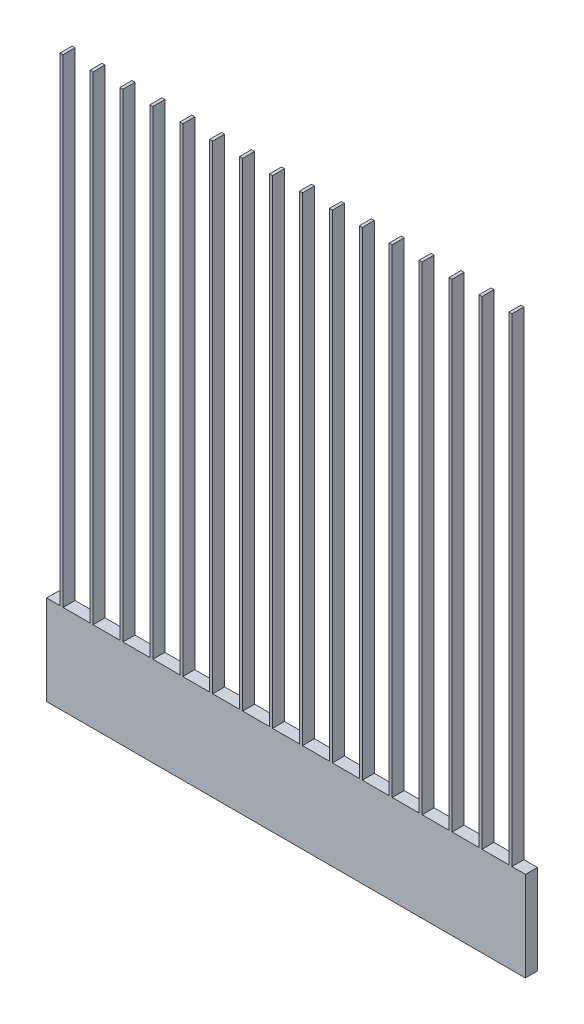
SolidWorks part; units mm, degrees
ref_plane "Front Plane" through (0, 0, 0) normal (1, 0, 0) x (0, 1, 0)
ref_plane "Top Plane" through (0, 0, 0) normal (0, 0, 1) x (0, 1, 0)
ref_plane "Right Plane" through (0, 0, 0) normal (0, 1, 0) x (-1, 0, 0)
sketch "Sketch1" plane through (0, 0, 0) normal (0, 0, 1) x (0, 1, 0)
  line L1 (0, 0) -> (10, 0) construction
  line L2 (0, 0) -> (0, -10) construction
  line L3 (0, -10) -> (10, -10) construction
  line L4 (10, 0) -> (10, -10) construction
  line L5 (0.5, -1) -> (2, -1)
  line L6 (0.5, -1) -> (0.5, -9)
  line L7 (0.5, -9) -> (2, -9)
  line L8 (2, -1) -> (2, -9)
  point P11 (1.8074, -10.4413)
  dimension "D1" = 10
  dimension "D2" = 10
  dimension "D3" = 1
  dimension "D4" = 1
  dimension "D5" = 0.5
  dimension "D6" = 1.5
extrude "Boss-Extrude1" add sketch "Sketch1" along normal blind 0.5
sketch "Sketch2" plane through (0, 2, 0) normal (0, 1, 0) x (-1, 0, 0)
  line L0 (-9, 0.5) -> (-1, 0.5) construction
  line L1 (-8.775, 0.5) -> (-8.725, 0.5)
  line L2 (-8.775, 0.5) -> (-8.775, 0)
  line L3 (-8.775, 0) -> (-8.725, 0)
  line L4 (-8.725, 0.5) -> (-8.725, 0)
  line L5 (0, 0) -> (-10, 0) construction
  line L6 (-8.275, 0.5) -> (-8.275, 0)
  line L7 (-8.225, 0.5) -> (-8.225, 0)
  line L8 (-8.275, 0) -> (-8.225, 0)
  line L9 (-8.275, 0.5) -> (-8.225, 0.5)
  line L10 (-7.775, 0.5) -> (-7.775, 0)
  line L11 (-7.725, 0.5) -> (-7.725, 0)
  line L12 (-7.775, 0) -> (-7.725, 0)
  line L13 (-7.775, 0.5) -> (-7.725, 0.5)
  line L14 (-7.275, 0.5) -> (-7.275, 0)
  line L15 (-7.225, 0.5) -> (-7.225, 0)
  line L16 (-7.275, 0) -> (-7.225, 0)
  line L17 (-7.275, 0.5) -> (-7.225, 0.5)
  line L18 (-6.775, 0.5) -> (-6.775, 0)
  line L19 (-6.725, 0.5) -> (-6.725, 0)
  line L20 (-6.775, 0) -> (-6.725, 0)
  line L21 (-6.775, 0.5) -> (-6.725, 0.5)
  line L22 (-6.275, 0.5) -> (-6.275, 0)
  line L23 (-6.225, 0.5) -> (-6.225, 0)
  line L24 (-6.275, 0) -> (-6.225, 0)
  line L25 (-6.275, 0.5) -> (-6.225, 0.5)
  line L26 (-5.775, 0.5) -> (-5.775, 0)
  line L27 (-5.725, 0.5) -> (-5.725, 0)
  line L28 (-5.775, 0) -> (-5.725, 0)
  line L29 (-5.775, 0.5) -> (-5.725, 0.5)
  line L30 (-5.275, 0.5) -> (-5.275, 0)
  line L31 (-5.225, 0.5) -> (-5.225, 0)
  line L32 (-5.275, 0) -> (-5.225, 0)
  line L33 (-5.275, 0.5) -> (-5.225, 0.5)
  line L34 (-4.775, 0.5) -> (-4.775, 0)
  line L35 (-4.725, 0.5) -> (-4.725, 0)
  line L36 (-4.775, 0) -> (-4.725, 0)
  line L37 (-4.775, 0.5) -> (-4.725, 0.5)
  line L38 (-4.275, 0.5) -> (-4.275, 0)
  line L39 (-4.225, 0.5) -> (-4.225, 0)
  line L40 (-4.275, 0) -> (-4.225, 0)
  line L41 (-4.275, 0.5) -> (-4.225, 0.5)
  line L42 (-3.775, 0.5) -> (-3.775, 0)
  line L43 (-3.725, 0.5) -> (-3.725, 0)
  line L44 (-3.775, 0) -> (-3.725, 0)
  line L45 (-3.775, 0.5) -> (-3.725, 0.5)
  line L46 (-3.275, 0.5) -> (-3.275, 0)
  line L47 (-3.225, 0.5) -> (-3.225, 0)
  line L48 (-3.275, 0) -> (-3.225, 0)
  line L49 (-3.275, 0.5) -> (-3.225, 0.5)
  line L50 (-2.775, 0.5) -> (-2.775, 0)
  line L51 (-2.725, 0.5) -> (-2.725, 0)
  line L52 (-2.775, 0) -> (-2.725, 0)
  line L53 (-2.775, 0.5) -> (-2.725, 0.5)
  line L54 (-2.275, 0.5) -> (-2.275, 0)
  line L55 (-2.225, 0.5) -> (-2.225, 0)
  line L56 (-2.275, 0) -> (-2.225, 0)
  line L57 (-2.275, 0.5) -> (-2.225, 0.5)
  line L58 (-1.775, 0.5) -> (-1.775, 0)
  line L59 (-1.725, 0.5) -> (-1.725, 0)
  line L60 (-1.775, 0) -> (-1.725, 0)
  line L61 (-1.775, 0.5) -> (-1.725, 0.5)
  line L62 (-1.275, 0.5) -> (-1.275, 0)
  line L63 (-1.225, 0.5) -> (-1.225, 0)
  line L64 (-1.275, 0) -> (-1.225, 0)
  line L65 (-1.275, 0.5) -> (-1.225, 0.5)
  line L68 (-9, 0.5) -> (-8.775, 0.5) construction
  line L69 (-1.225, 0.5) -> (-1, 0.5) construction
  dimension "D1" = 0.05
  dimension "D3" = 0.5
  dimension "D2" = 16
extrude "Boss-Extrude2" add sketch "Sketch2" along normal up to vertex (8 mm away) up to point (10, 10, 0)
sketch "Sketch3" plane through (0, 0.5, 0) normal (0, -1, 0) x (1, 0, 0)
  line L0 (9, 0.5) -> (9, 0) construction
  line L1 (1, 0.3) -> (9, 0.3)
  line L2 (1, 0.3) -> (1, 0)
  line L3 (1, 0) -> (9, 0)
  line L4 (9, 0.3) -> (9, 0)
  point P4 (0, 0)
  point P7 (0, 0)
  dimension "D1" = 0.3
extrude "Cut-Extrude1" cut sketch "Sketch3" against normal through all
